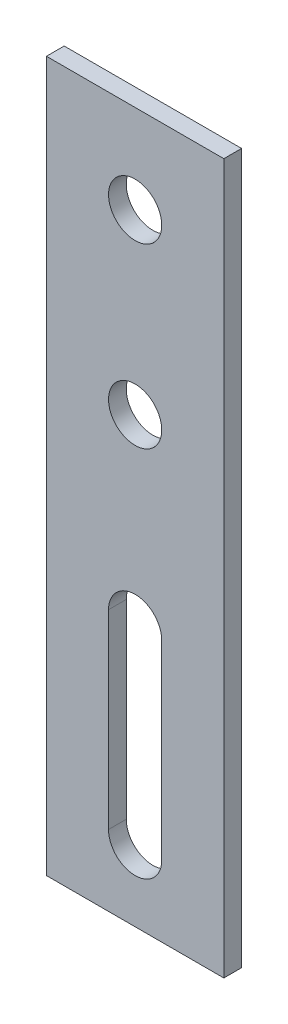
SolidWorks part; units mm, degrees
ref_plane "Płaszczyzna przednia" through (0, 0, 0) normal (0, 0, 1) x (1, 0, 0)
ref_plane "Płaszczyzna górna" through (0, 0, 0) normal (0, 1, 0) x (1, 0, 0)
ref_plane "Płaszczyzna prawa" through (0, 0, 0) normal (1, 0, 0) x (0, 0, -1)
sketch "Szkic1" plane through (0, 0, 0) normal (0, 0, 1) x (1, 0, 0)
  line L0 (-3.3589, -24.1839) -> (-3.3589, -2.7227) construction
  line L1 (-13.3589, 47.8161) -> (6.6411, 47.8161)
  line L2 (-13.3589, 47.8161) -> (-13.3589, -32.1839)
  line L3 (-13.3589, -32.1839) -> (6.6411, -32.1839)
  line L4 (6.6411, 47.8161) -> (6.6411, -32.1839)
  line L5 (-6.3589, -24.1839) -> (-6.3589, -2.7227)
  line L6 (-0.3589, -24.1839) -> (-0.3589, -2.7227)
  circle A0 centre (-3.3589, 37.8161) radius 3
  circle A1 centre (-3.3589, 17.8161) radius 3
  arc A2 (-6.3589, -24.1839) -> (-0.3589, -24.1839) centre (-3.3589, -24.1839) ccw
  arc A3 (-0.3589, -2.7227) -> (-6.3589, -2.7227) centre (-3.3589, -2.7227) ccw
  point P10 (-3.3589, -13.4533)
  dimension "D3" = 6
  dimension "D4" = 6
  dimension "D10" = 3
  dimension "D1" = 20
  dimension "D2" = 80
  dimension "D5" = 10
  dimension "D6" = 10
  dimension "D7" = 20
  dimension "D8" = 10
  dimension "D9" = 10
  dimension "D11" = 8
extrude "Dodanie-wyciągnięcie1" add sketch "Szkic1" along normal blind 2
